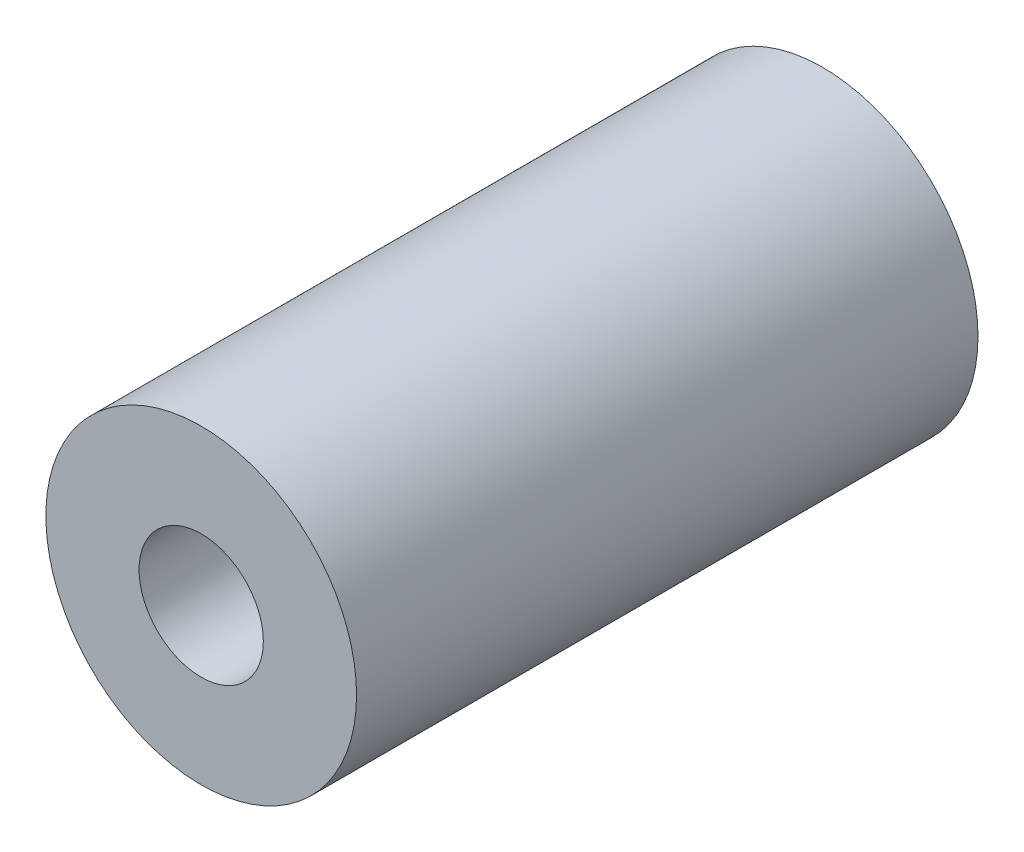
SolidWorks part; units mm, degrees
material "1060 合金"
ref_plane "前视基准面" through (0, 0, 0) normal (0, 0, 1) x (1, 0, 0)
ref_plane "上视基准面" through (0, 0, 0) normal (0, 1, 0) x (1, 0, 0)
ref_plane "右视基准面" through (0, 0, 0) normal (1, 0, 0) x (0, 0, -1)
other "Configuration Table"
sketch "草图1" plane through (0, 0, 0) normal (0, 0, 1) x (1, 0, 0)
  circle A0 centre (0, 0) radius 2
  circle A1 centre (0, 0) radius 5
  dimension "D1" = 4
  dimension "D2" = 10
extrude "凸台-拉伸1" add sketch "草图1" along normal blind 20
